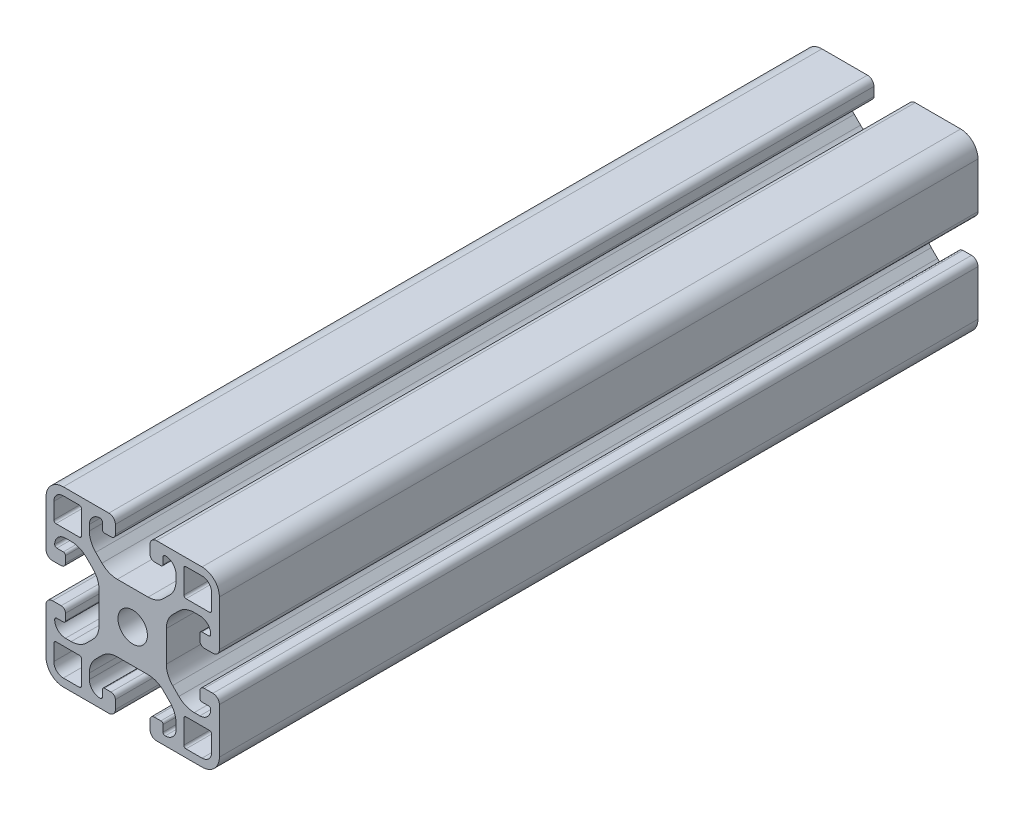
SolidWorks part; units mm, degrees
ref_plane "Plan de face" through (0, 0, 0) normal (0, 0, 1) x (1, 0, 0)
ref_plane "Plan de dessus" through (0, 0, 0) normal (0, 1, 0) x (1, 0, 0)
ref_plane "Plan de droite" through (0, 0, 0) normal (1, 0, 0) x (0, 0, -1)
ref_plane "Plan1" through (0, 0, -30) normal (0, 0, -1) x (-1, 0, 0)
sketch "Esquisse1" plane through (0, 0, -30) normal (0, 0, -1) x (-1, 0, 0)
  line L0 (-4.5, 15) -> (-4.5, 13.5)
  line L1 (-4, 13) -> (-2.5, 13)
  line L2 (-4.5, 10) -> (-5.8076, 10)
  line L3 (-9.3431, 11.4645) -> (-10.7855, 12.9069)
  line L4 (-12.25, 16.4424) -> (-12.25, 23.5576)
  line L5 (-10.7855, 27.0931) -> (-9.3431, 28.5355)
  line L6 (-5.8076, 30) -> (-4.5, 30)
  line L7 (-2.5, 27) -> (-4, 27)
  line L8 (-4.5, 26.5) -> (-4.5, 25)
  line L9 (-3.5, 24) -> (-1.5, 24)
  line L10 (0, 25.5) -> (0, 36)
  line L11 (-4, 40) -> (-14.5, 40)
  line L12 (-16, 38.5) -> (-16, 36.5)
  line L13 (-15, 35.5) -> (-13.5, 35.5)
  line L14 (-13, 36) -> (-13, 37.5)
  line L15 (-10, 35.5) -> (-10, 34.1924)
  line L16 (-11.4645, 30.6569) -> (-12.9069, 29.2145)
  line L17 (-16.4424, 27.75) -> (-23.5576, 27.75)
  line L18 (-27.0931, 29.2145) -> (-28.5355, 30.6569)
  line L19 (-30, 34.1924) -> (-30, 35.5)
  line L20 (-27, 37.5) -> (-27, 36)
  line L21 (-26.5, 35.5) -> (-25, 35.5)
  line L22 (-24, 36.5) -> (-24, 38.5)
  line L23 (-25.5, 40) -> (-36, 40)
  line L24 (-40, 36) -> (-40, 25.5)
  line L25 (-38.5, 24) -> (-36.5, 24)
  line L26 (-35.5, 25) -> (-35.5, 26.5)
  line L27 (-36, 27) -> (-37.5, 27)
  line L28 (-35.5, 30) -> (-34.1924, 30)
  line L29 (-30.6569, 28.5355) -> (-29.2145, 27.0931)
  line L30 (-27.75, 23.5576) -> (-27.75, 16.4424)
  line L31 (-29.2145, 12.9069) -> (-30.6569, 11.4645)
  line L32 (-34.1924, 10) -> (-35.5, 10)
  line L33 (-37.5, 13) -> (-36, 13)
  line L34 (-35.5, 13.5) -> (-35.5, 15)
  line L35 (-36.5, 16) -> (-38.5, 16)
  line L36 (-40, 14.5) -> (-40, 4)
  line L37 (-36, 0) -> (-25.5, 0)
  line L38 (-24, 1.5) -> (-24, 3.5)
  line L39 (-25, 4.5) -> (-26.5, 4.5)
  line L40 (-27, 4) -> (-27, 2.5)
  line L41 (-30, 4.5) -> (-30, 5.8076)
  line L42 (-28.5355, 9.3431) -> (-27.0931, 10.7855)
  line L43 (-23.5576, 12.25) -> (-16.4424, 12.25)
  line L44 (-12.9069, 10.7855) -> (-11.4645, 9.3431)
  line L45 (-10, 5.8076) -> (-10, 4.5)
  line L46 (-13, 2.5) -> (-13, 4)
  line L47 (-13.5, 4.5) -> (-15, 4.5)
  line L48 (-16, 3.5) -> (-16, 1.5)
  line L49 (-14.5, 0) -> (-4, 0)
  line L50 (0, 4) -> (0, 14.5)
  line L51 (-1.5, 16) -> (-3.5, 16)
  line L52 (-4, 1.8) -> (-7.7, 1.8)
  line L53 (-8.2, 2.3) -> (-8.2, 7.7)
  line L54 (-7.7, 8.2) -> (-2.3, 8.2)
  line L55 (-1.8, 7.7) -> (-1.8, 4)
  line L56 (-38.2, 4) -> (-38.2, 7.7)
  line L57 (-37.7, 8.2) -> (-32.3, 8.2)
  line L58 (-31.8, 7.7) -> (-31.8, 2.3)
  line L59 (-32.3, 1.8) -> (-36, 1.8)
  line L60 (-36, 38.2) -> (-32.3, 38.2)
  line L61 (-31.8, 37.7) -> (-31.8, 32.3)
  line L62 (-32.3, 31.8) -> (-37.7, 31.8)
  line L63 (-38.2, 32.3) -> (-38.2, 36)
  line L64 (-1.8, 36) -> (-1.8, 32.3)
  line L65 (-2.3, 31.8) -> (-7.7, 31.8)
  line L66 (-8.2, 32.3) -> (-8.2, 37.7)
  line L67 (-7.7, 38.2) -> (-4, 38.2)
  arc A0 (-4.5, 13.5) -> (-4, 13) centre (-4, 13.5) ccw
  arc A1 (-2.5, 13) -> (-2, 12.5) centre (-2.5, 12.5) cw
  arc A2 (-2, 12.5) -> (-4.5, 10) centre (-4.5, 12.5) cw
  arc A3 (-5.8076, 10) -> (-9.3431, 11.4645) centre (-5.8076, 15) cw
  arc A4 (-10.7855, 12.9069) -> (-12.25, 16.4424) centre (-7.25, 16.4424) cw
  arc A5 (-12.25, 23.5576) -> (-10.7855, 27.0931) centre (-7.25, 23.5576) cw
  arc A6 (-9.3431, 28.5355) -> (-5.8076, 30) centre (-5.8076, 25) cw
  arc A7 (-4.5, 30) -> (-2, 27.5) centre (-4.5, 27.5) cw
  arc A8 (-2, 27.5) -> (-2.5, 27) centre (-2.5, 27.5) cw
  arc A9 (-4, 27) -> (-4.5, 26.5) centre (-4, 26.5) ccw
  arc A10 (-4.5, 25) -> (-3.5, 24) centre (-3.5, 25) ccw
  arc A11 (-1.5, 24) -> (0, 25.5) centre (-1.5, 25.5) ccw
  arc A12 (0, 36) -> (-4, 40) centre (-4, 36) ccw
  arc A13 (-14.5, 40) -> (-16, 38.5) centre (-14.5, 38.5) ccw
  arc A14 (-16, 36.5) -> (-15, 35.5) centre (-15, 36.5) ccw
  arc A15 (-13.5, 35.5) -> (-13, 36) centre (-13.5, 36) ccw
  arc A16 (-13, 37.5) -> (-12.5, 38) centre (-12.5, 37.5) cw
  arc A17 (-12.5, 38) -> (-10, 35.5) centre (-12.5, 35.5) cw
  arc A18 (-10, 34.1924) -> (-11.4645, 30.6569) centre (-15, 34.1924) cw
  arc A19 (-12.9069, 29.2145) -> (-16.4424, 27.75) centre (-16.4424, 32.75) cw
  arc A20 (-23.5576, 27.75) -> (-27.0931, 29.2145) centre (-23.5576, 32.75) cw
  arc A21 (-28.5355, 30.6569) -> (-30, 34.1924) centre (-25, 34.1924) cw
  arc A22 (-30, 35.5) -> (-27.5, 38) centre (-27.5, 35.5) cw
  arc A23 (-27.5, 38) -> (-27, 37.5) centre (-27.5, 37.5) cw
  arc A24 (-27, 36) -> (-26.5, 35.5) centre (-26.5, 36) ccw
  arc A25 (-25, 35.5) -> (-24, 36.5) centre (-25, 36.5) ccw
  arc A26 (-24, 38.5) -> (-25.5, 40) centre (-25.5, 38.5) ccw
  arc A27 (-36, 40) -> (-40, 36) centre (-36, 36) ccw
  arc A28 (-40, 25.5) -> (-38.5, 24) centre (-38.5, 25.5) ccw
  arc A29 (-36.5, 24) -> (-35.5, 25) centre (-36.5, 25) ccw
  arc A30 (-35.5, 26.5) -> (-36, 27) centre (-36, 26.5) ccw
  arc A31 (-37.5, 27) -> (-38, 27.5) centre (-37.5, 27.5) cw
  arc A32 (-38, 27.5) -> (-35.5, 30) centre (-35.5, 27.5) cw
  arc A33 (-34.1924, 30) -> (-30.6569, 28.5355) centre (-34.1924, 25) cw
  arc A34 (-29.2145, 27.0931) -> (-27.75, 23.5576) centre (-32.75, 23.5576) cw
  arc A35 (-27.75, 16.4424) -> (-29.2145, 12.9069) centre (-32.75, 16.4424) cw
  arc A36 (-30.6569, 11.4645) -> (-34.1924, 10) centre (-34.1924, 15) cw
  arc A37 (-35.5, 10) -> (-38, 12.5) centre (-35.5, 12.5) cw
  arc A38 (-38, 12.5) -> (-37.5, 13) centre (-37.5, 12.5) cw
  arc A39 (-36, 13) -> (-35.5, 13.5) centre (-36, 13.5) ccw
  arc A40 (-35.5, 15) -> (-36.5, 16) centre (-36.5, 15) ccw
  arc A41 (-38.5, 16) -> (-40, 14.5) centre (-38.5, 14.5) ccw
  arc A42 (-40, 4) -> (-36, 0) centre (-36, 4) ccw
  arc A43 (-25.5, 0) -> (-24, 1.5) centre (-25.5, 1.5) ccw
  arc A44 (-24, 3.5) -> (-25, 4.5) centre (-25, 3.5) ccw
  arc A45 (-26.5, 4.5) -> (-27, 4) centre (-26.5, 4) ccw
  arc A46 (-27, 2.5) -> (-27.5, 2) centre (-27.5, 2.5) cw
  arc A47 (-27.5, 2) -> (-30, 4.5) centre (-27.5, 4.5) cw
  arc A48 (-30, 5.8076) -> (-28.5355, 9.3431) centre (-25, 5.8076) cw
  arc A49 (-27.0931, 10.7855) -> (-23.5576, 12.25) centre (-23.5576, 7.25) cw
  arc A50 (-16.4424, 12.25) -> (-12.9069, 10.7855) centre (-16.4424, 7.25) cw
  arc A51 (-11.4645, 9.3431) -> (-10, 5.8076) centre (-15, 5.8076) cw
  arc A52 (-10, 4.5) -> (-12.5, 2) centre (-12.5, 4.5) cw
  arc A53 (-12.5, 2) -> (-13, 2.5) centre (-12.5, 2.5) cw
  arc A54 (-13, 4) -> (-13.5, 4.5) centre (-13.5, 4) ccw
  arc A55 (-15, 4.5) -> (-16, 3.5) centre (-15, 3.5) ccw
  arc A56 (-16, 1.5) -> (-14.5, 0) centre (-14.5, 1.5) ccw
  arc A57 (-4, 0) -> (0, 4) centre (-4, 4) ccw
  arc A58 (0, 14.5) -> (-1.5, 16) centre (-1.5, 14.5) ccw
  arc A59 (-3.5, 16) -> (-4.5, 15) centre (-3.5, 15) ccw
  circle A60 centre (-20, 20) radius 3.4
  arc A61 (-1.8, 4) -> (-4, 1.8) centre (-4, 4) cw
  arc A62 (-7.7, 1.8) -> (-8.2, 2.3) centre (-7.7, 2.3) cw
  arc A63 (-8.2, 7.7) -> (-7.7, 8.2) centre (-7.7, 7.7) cw
  arc A64 (-2.3, 8.2) -> (-1.8, 7.7) centre (-2.3, 7.7) cw
  arc A65 (-36, 1.8) -> (-38.2, 4) centre (-36, 4) cw
  arc A66 (-38.2, 7.7) -> (-37.7, 8.2) centre (-37.7, 7.7) cw
  arc A67 (-32.3, 8.2) -> (-31.8, 7.7) centre (-32.3, 7.7) cw
  arc A68 (-31.8, 2.3) -> (-32.3, 1.8) centre (-32.3, 2.3) cw
  arc A69 (-38.2, 36) -> (-36, 38.2) centre (-36, 36) cw
  arc A70 (-32.3, 38.2) -> (-31.8, 37.7) centre (-32.3, 37.7) cw
  arc A71 (-31.8, 32.3) -> (-32.3, 31.8) centre (-32.3, 32.3) cw
  arc A72 (-37.7, 31.8) -> (-38.2, 32.3) centre (-37.7, 32.3) cw
  arc A73 (-4, 38.2) -> (-1.8, 36) centre (-4, 36) cw
  arc A74 (-1.8, 32.3) -> (-2.3, 31.8) centre (-2.3, 32.3) cw
  arc A75 (-7.7, 31.8) -> (-8.2, 32.3) centre (-7.7, 32.3) cw
  arc A76 (-8.2, 37.7) -> (-7.7, 38.2) centre (-7.7, 37.7) cw
extrude "Boss.-Extru.1" add sketch "Esquisse1" against normal blind 175
